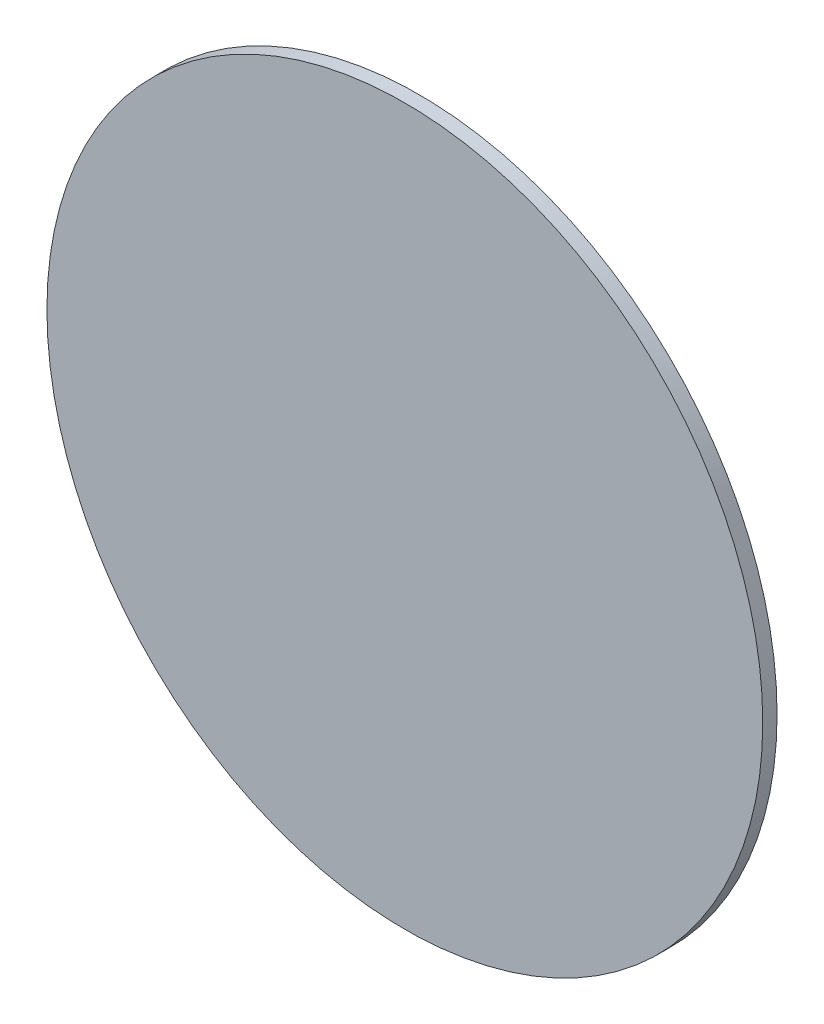
SolidWorks part; units mm, degrees
ref_plane "Front" through (0, 0, 0) normal (0, 0, 1) x (1, 0, 0)
ref_plane "Top" through (0, 0, 0) normal (0, 1, 0) x (1, 0, 0)
ref_plane "Right" through (0, 0, 0) normal (1, 0, 0) x (0, 0, -1)
sketch "Esquisse1" plane through (0, 0, 0) normal (0, 0, 1) x (1, 0, 0)
  circle A0 centre (0, 0) radius 11.5
extrude "Boss.-Extru.1" add sketch "Esquisse1" along normal blind 6
sketch "Esquisse2" plane through (0, 0, 6) normal (0, 0, 1) x (1, 0, 0)
  circle A0 centre (0, 0) radius 25
  circle A1 centre (0, 0) radius 7.5
  dimension "D1" = 50
extrude "Boss.-Extru.2" add sketch "Esquisse2" against normal blind 1
